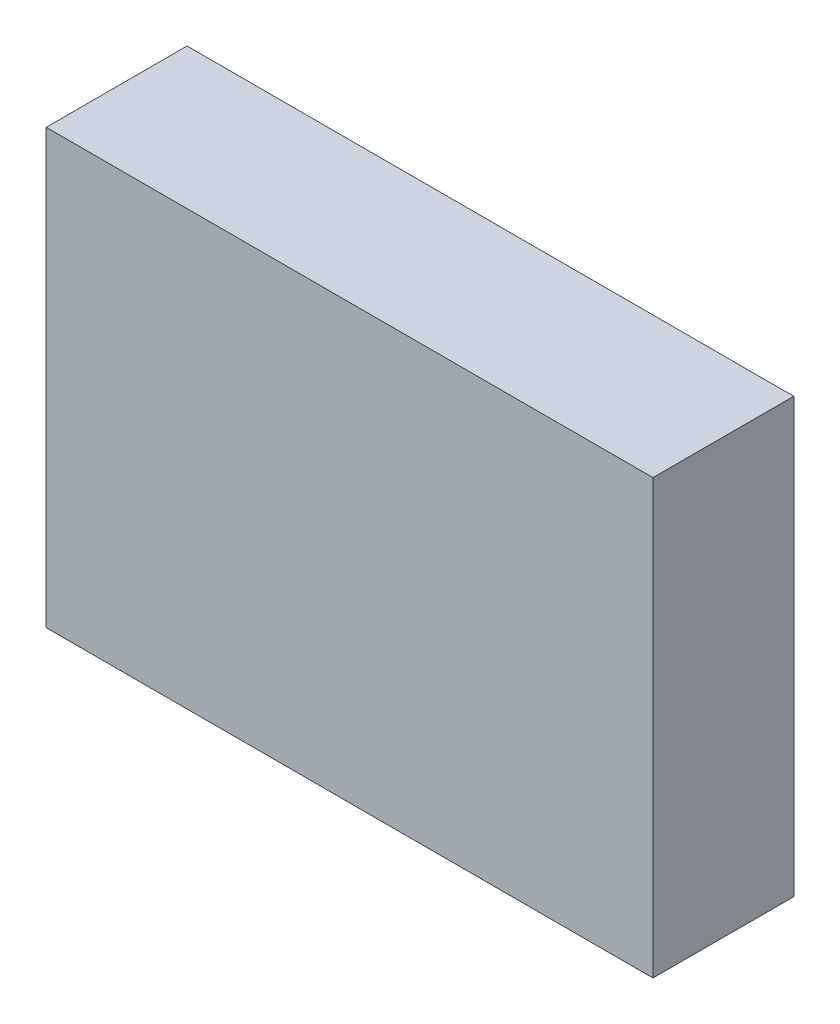
SolidWorks part; units mm, degrees
ref_plane "정면" through (0, 0, 0) normal (0, 0, 1) x (1, 0, 0)
ref_plane "윗면" through (0, 0, 0) normal (0, 1, 0) x (1, 0, 0)
ref_plane "우측면" through (0, 0, 0) normal (1, 0, 0) x (0, 0, -1)
sketch "스케치2" plane through (0, 0, 0) normal (0, 0, 1) x (1, 0, 0)
  line L1 (280, 200) -> (-280, 200)
  line L2 (280, 200) -> (280, -200)
  line L3 (280, -200) -> (-280, -200)
  line L4 (-280, 200) -> (-280, -200)
  line L5 (280, 200) -> (-280, -200) construction
  line L6 (280, -200) -> (-280, 200) construction
  point P0 (0, 0)
  dimension "D1" = 560
  dimension "D2" = 400
extrude "보스-돌출1" add sketch "스케치2" along normal blind 130
